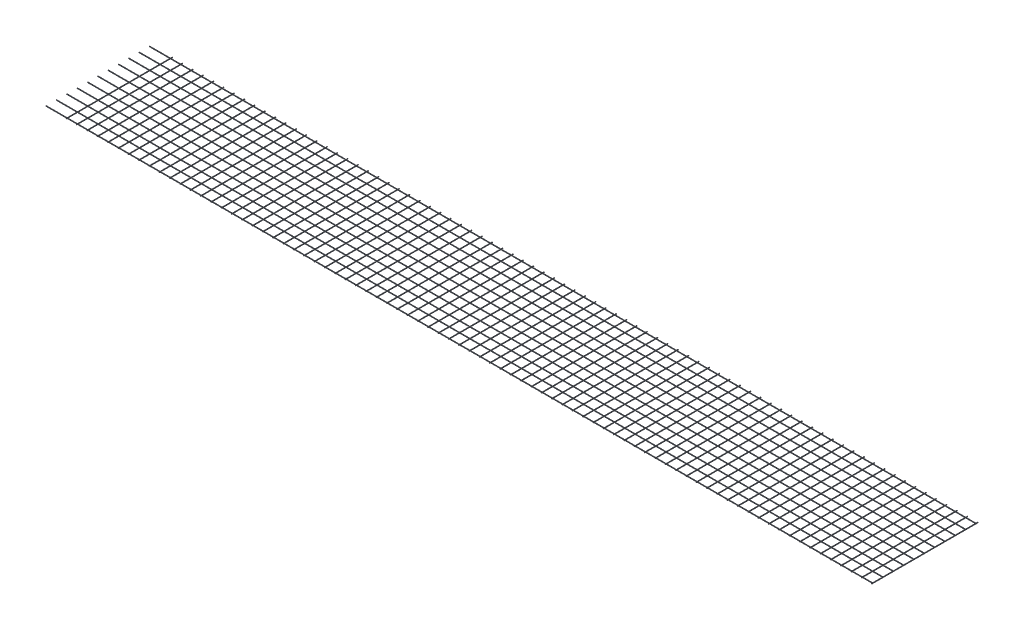
SolidWorks part; units mm, degrees
ref_plane "Front Plane" through (0, 0, 0) normal (0, 0, 1) x (1, 0, 0)
ref_plane "Top Plane" through (0, 0, 0) normal (0, 1, 0) x (1, 0, 0)
ref_plane "Right Plane" through (0, 0, 0) normal (1, 0, 0) x (0, 0, -1)
sketch "Sketch1" plane through (0, 0, 0) normal (0, 0, 1) x (1, 0, 0)
  line L0 (55, 0) -> (-55, 0) construction
  circle A0 centre (-76.3507, 0) radius 2.5
  circle A1 centre (23.6493, 0) radius 2.5
  circle A2 centre (123.6493, 0) radius 2.5
  circle A3 centre (223.6493, 0) radius 2.5
  circle A4 centre (323.6493, 0) radius 2.5
  circle A5 centre (423.6493, 0) radius 2.5
  circle A6 centre (523.6493, 0) radius 2.5
  circle A7 centre (623.6493, 0) radius 2.5
  circle A8 centre (723.6493, 0) radius 2.5
  circle A9 centre (823.6493, 0) radius 2.5
  circle A10 centre (923.6493, 0) radius 2.5
  circle A11 centre (1023.6493, 0) radius 2.5
  circle A12 centre (1123.6493, 0) radius 2.5
  circle A13 centre (1223.6493, 0) radius 2.5
  circle A14 centre (1323.6493, 0) radius 2.5
  circle A15 centre (1423.6493, 0) radius 2.5
  circle A16 centre (1523.6493, 0) radius 2.5
  circle A17 centre (1623.6493, 0) radius 2.5
  circle A18 centre (1723.6493, 0) radius 2.5
  circle A19 centre (1823.6493, 0) radius 2.5
  circle A20 centre (1923.6493, 0) radius 2.5
  circle A21 centre (2023.6493, 0) radius 2.5
  circle A22 centre (2123.6493, 0) radius 2.5
  circle A23 centre (2223.6493, 0) radius 2.5
  circle A24 centre (2323.6493, 0) radius 2.5
  circle A25 centre (2423.6493, 0) radius 2.5
  circle A26 centre (2523.6493, 0) radius 2.5
  circle A27 centre (2623.6493, 0) radius 2.5
  circle A28 centre (2723.6493, 0) radius 2.5
  circle A29 centre (2823.6493, 0) radius 2.5
  circle A30 centre (2923.6493, 0) radius 2.5
  circle A31 centre (3023.6493, 0) radius 2.5
  circle A32 centre (3123.6493, 0) radius 2.5
  circle A33 centre (3223.6493, 0) radius 2.5
  circle A34 centre (3323.6493, 0) radius 2.5
  circle A35 centre (3423.6493, 0) radius 2.5
  circle A36 centre (3523.6493, 0) radius 2.5
  circle A37 centre (3623.6493, 0) radius 2.5
  circle A38 centre (3723.6493, 0) radius 2.5
  circle A39 centre (3823.6493, 0) radius 2.5
  circle A40 centre (3923.6493, 0) radius 2.5
  circle A41 centre (4023.6493, 0) radius 2.5
  circle A42 centre (4123.6493, 0) radius 2.5
  circle A43 centre (4223.6493, 0) radius 2.5
  circle A44 centre (4323.6493, 0) radius 2.5
  circle A45 centre (4423.6493, 0) radius 2.5
  circle A46 centre (4523.6493, 0) radius 2.5
  circle A47 centre (4623.6493, 0) radius 2.5
  circle A48 centre (4723.6493, 0) radius 2.5
  circle A49 centre (4823.6493, 0) radius 2.5
  circle A50 centre (4923.6493, 0) radius 2.5
  circle A51 centre (5023.6493, 0) radius 2.5
  circle A52 centre (5123.6493, 0) radius 2.5
  circle A53 centre (5223.6493, 0) radius 2.5
  circle A54 centre (5323.6493, 0) radius 2.5
  circle A55 centre (5423.6493, 0) radius 2.5
  circle A56 centre (5523.6493, 0) radius 2.5
  circle A57 centre (5623.6493, 0) radius 2.5
  circle A58 centre (5723.6493, 0) radius 2.5
  circle A59 centre (5823.6493, 0) radius 2.5
  circle A60 centre (5923.6493, 0) radius 2.5
  circle A61 centre (6023.6493, 0) radius 2.5
  circle A62 centre (6123.6493, 0) radius 2.5
  circle A63 centre (6223.6493, 0) radius 2.5
  circle A64 centre (6323.6493, 0) radius 2.5
  circle A65 centre (6423.6493, 0) radius 2.5
  circle A66 centre (6523.6493, 0) radius 2.5
  circle A67 centre (6623.6493, 0) radius 2.5
  circle A68 centre (6723.6493, 0) radius 2.5
  circle A69 centre (6823.6493, 0) radius 2.5
  circle A70 centre (6923.6493, 0) radius 2.5
  circle A71 centre (7023.6493, 0) radius 2.5
  circle A72 centre (7123.6493, 0) radius 2.5
  circle A73 centre (7223.6493, 0) radius 2.5
  circle A74 centre (7323.6493, 0) radius 2.5
  circle A75 centre (7423.6493, 0) radius 2.5
  circle A76 centre (7523.6493, 0) radius 2.5
  circle A77 centre (7623.6493, 0) radius 2.5
  circle A78 centre (7723.6493, 0) radius 2.5
  dimension "D1" = 79
extrude "Boss-Extrude1" add sketch "Sketch1" along normal blind 1025
ref_plane "Plane1" through (7726.1493, 0, 0) normal (1, 0, 0) x (0, 0, -1)
sketch "Sketch2" plane through (7726.1493, 0, 0) normal (1, 0, 0) x (0, 0, -1)
  circle A0 centre (-1022.5, 5) radius 2.5
  circle A1 centre (-922.5, 5) radius 2.5
  circle A2 centre (-822.5, 5) radius 2.5
  circle A3 centre (-722.5, 5) radius 2.5
  circle A4 centre (-622.5, 5) radius 2.5
  circle A5 centre (-522.5, 5) radius 2.5
  circle A6 centre (-422.5, 5) radius 2.5
  circle A7 centre (-322.5, 5) radius 2.5
  circle A8 centre (-222.5, 5) radius 2.5
  circle A9 centre (-122.5, 5) radius 2.5
  circle A10 centre (-22.5, 5) radius 2.5
  dimension "D1" = 11
extrude "Boss-Extrude2" add sketch "Sketch2" against normal blind 8000 separate body
